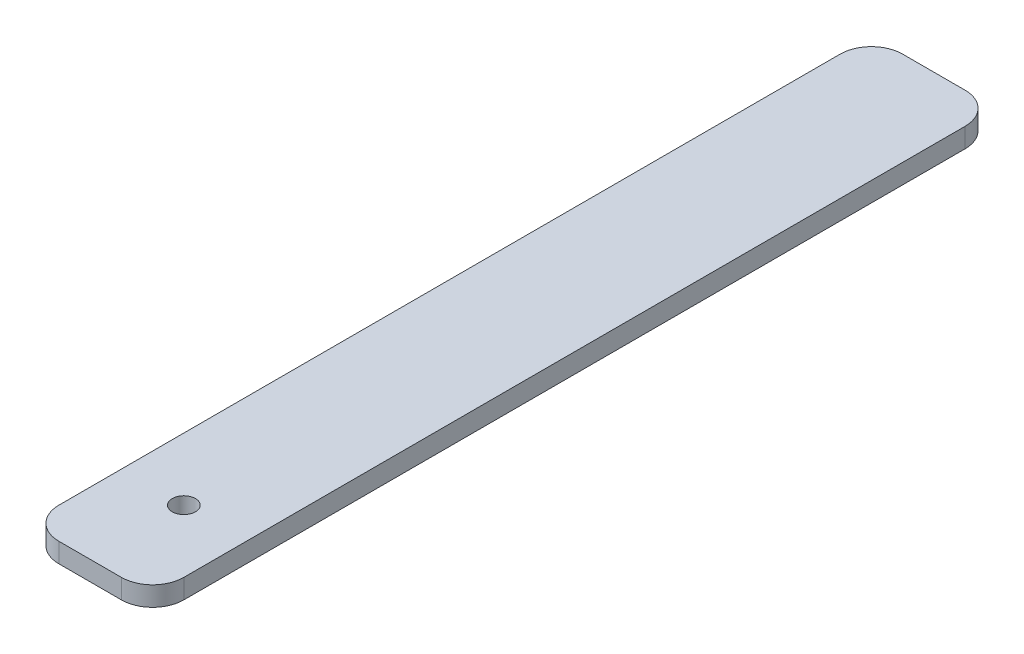
SolidWorks part; units mm, degrees
ref_plane "Front Plane" through (0, 0, 0) normal (0, 0, 1) x (1, 0, 0)
ref_plane "Top Plane" through (0, 0, 0) normal (0, 1, 0) x (1, 0, 0)
ref_plane "Right Plane" through (0, 0, 0) normal (1, 0, 0) x (0, 0, -1)
sketch "Sketch1" plane through (0, 0, 0) normal (0, 1, 0) x (1, 0, 0)
  line L0 (5.08, 0) -> (5.08, 68.58) construction
  line L1 (0, 0) -> (10.16, 0)
  line L2 (0, 0) -> (0, 68.58)
  line L3 (0, 68.58) -> (10.16, 68.58)
  line L4 (10.16, 0) -> (10.16, 68.58)
  circle A0 centre (5.08, 7.62) radius 0.9398
  dimension "D1" = 1.8796
  dimension "D2" = 7.62
  dimension "D3" = 68.58
  dimension "D4" = 10.16
extrude "Boss-Extrude1" add sketch "Sketch1" along normal blind 1.5875
fillet "Fillet1" radius 2.54 4 edges at (0, 0.7937, -68.58) (10.16, 0.7937, -68.58) (10.16, 0.7937, 0) (0, 0.7937, 0)
